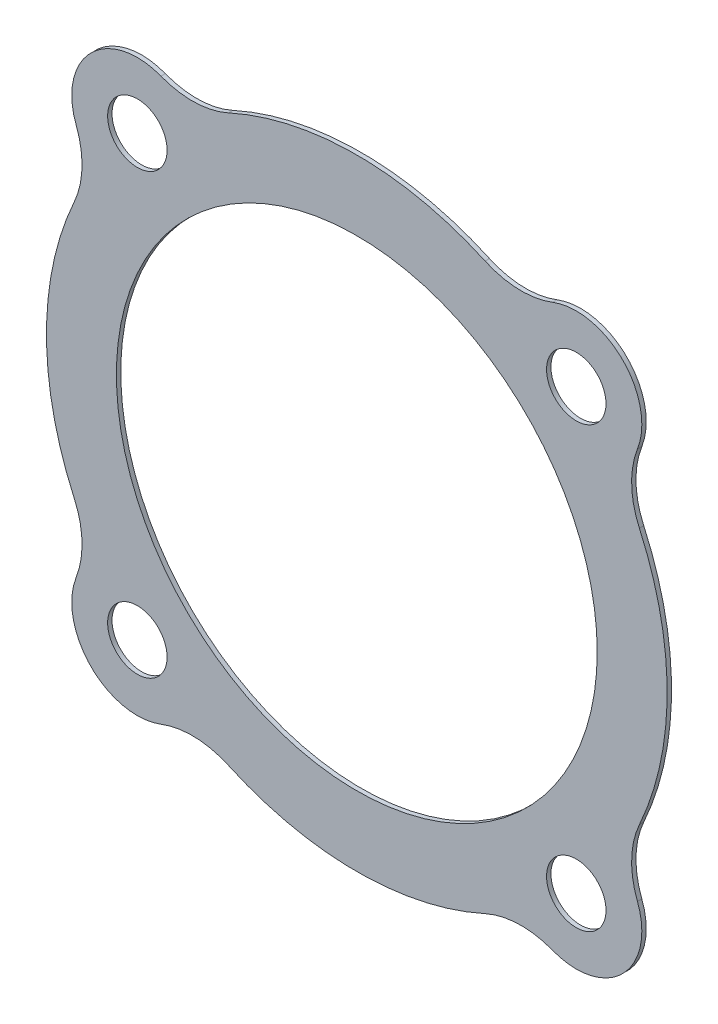
SolidWorks part; units mm, degrees
material "VITON"
ref_plane "Front" through (0, 0, 0) normal (0, 0, 1) x (1, 0, 0)
ref_plane "Top" through (0, 0, 0) normal (0, 1, 0) x (1, 0, 0)
ref_plane "Right" through (0, 0, 0) normal (1, 0, 0) x (0, 0, -1)
sketch "Sketch1" plane through (0, 0, 0) normal (0, 0, 1) x (1, 0, 0)
  line L1 (-31.8799, -31.8799) -> (31.8799, -31.8799) construction
  line L2 (-31.8799, -31.8799) -> (-31.8799, 31.8799) construction
  line L3 (-31.8799, 31.8799) -> (31.8799, 31.8799) construction
  line L4 (31.8799, -31.8799) -> (31.8799, 31.8799) construction
  line L5 (-31.8799, -31.8799) -> (31.8799, 31.8799) construction
  line L6 (-31.8799, 31.8799) -> (31.8799, -31.8799) construction
  arc A0 (-41.0531, 18.636) -> (-41.0531, -18.636) centre (0, 0) ccw
  circle A1 centre (0, 0) radius 34.925
  arc A2 (-28.4538, 40.7674) -> (-40.7674, 28.4538) centre (-31.8799, 31.8799) ccw
  arc A3 (41.0531, -18.636) -> (41.0531, 18.636) centre (0, 0) ccw
  arc A4 (28.4538, -40.7674) -> (40.7674, -28.4538) centre (31.8799, -31.8799) ccw
  arc A5 (-40.7674, -28.4538) -> (-28.4538, -40.7674) centre (-31.8799, -31.8799) ccw
  circle A6 centre (31.8799, 31.8799) radius 4.318
  circle A7 centre (-31.8799, 31.8799) radius 4.318
  circle A8 centre (-31.8799, -31.8799) radius 4.318
  circle A9 centre (31.8799, -31.8799) radius 4.318
  arc A10 (18.636, 41.0531) -> (-18.636, 41.0531) centre (0, 0) ccw
  arc A11 (40.7674, 28.4538) -> (28.4538, 40.7674) centre (31.8799, 31.8799) ccw
  arc A12 (18.636, 41.0531) -> (28.4538, 40.7674) centre (23.8856, 52.6173) ccw
  arc A13 (-18.636, -41.0531) -> (18.636, -41.0531) centre (0, 0) ccw
  arc A14 (41.0531, 18.636) -> (40.7674, 28.4538) centre (52.6173, 23.8856) cw
  arc A15 (40.7674, -28.4538) -> (41.0531, -18.636) centre (52.6173, -23.8856) cw
  arc A16 (18.636, -41.0531) -> (28.4538, -40.7674) centre (23.8856, -52.6173) cw
  arc A17 (-28.4538, -40.7674) -> (-18.636, -41.0531) centre (-23.8856, -52.6173) cw
  arc A18 (-40.7674, -28.4538) -> (-41.0531, -18.636) centre (-52.6173, -23.8856) ccw
  arc A19 (-40.7674, 28.4538) -> (-41.0531, 18.636) centre (-52.6173, 23.8856) cw
  arc A20 (-28.4538, 40.7674) -> (-18.636, 41.0531) centre (-23.8856, 52.6173) ccw
  point P25 (37.866, -24.4709)
  dimension "D1" = 90.17
  dimension "D2" = 69.85
  dimension "D3" = 19.05
  dimension "D4" = 8.636
  dimension "D5" = 12.7
extrude "Boss-Extrude1" add sketch "Sketch1" along normal blind 0.635
